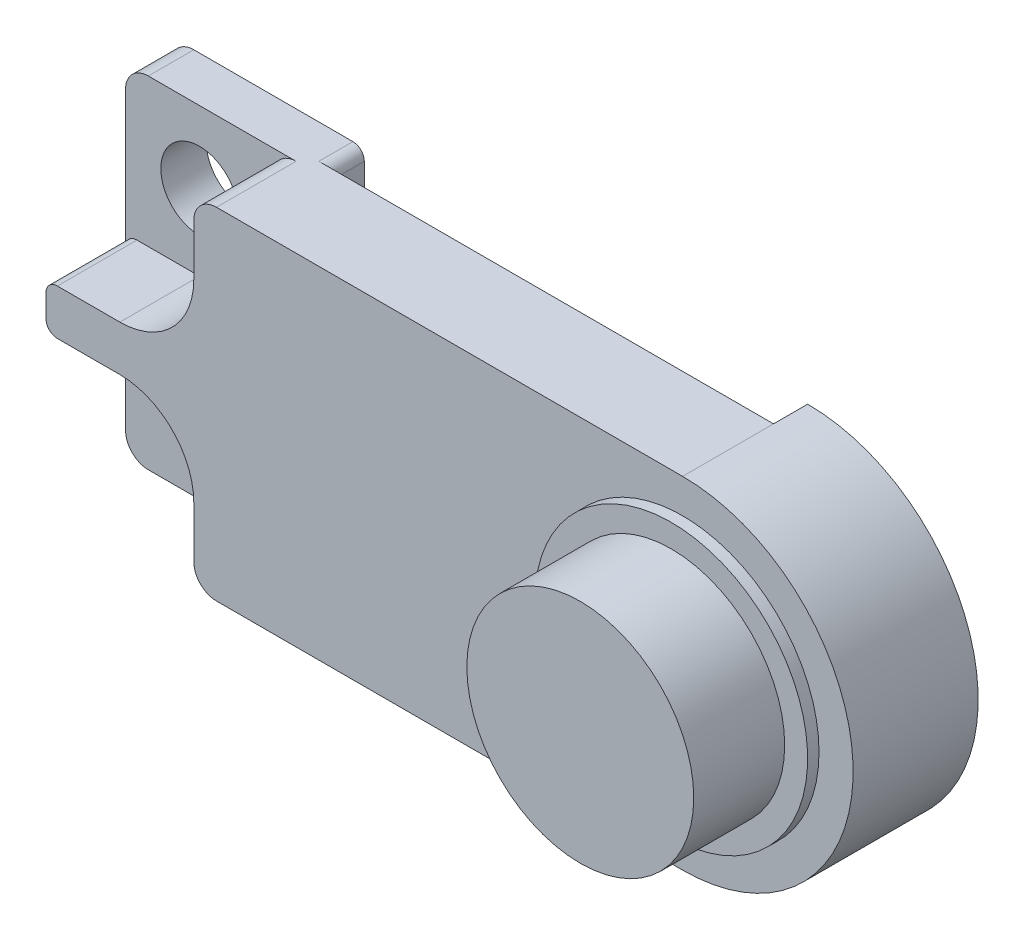
SolidWorks part; units mm, degrees
ref_plane "前视基准面" through (0, 0, 0) normal (0, 0, 1) x (1, 0, 0)
ref_plane "上视基准面" through (0, 0, 0) normal (0, 1, 0) x (1, 0, 0)
ref_plane "右视基准面" through (0, 0, 0) normal (1, 0, 0) x (0, 0, -1)
ref_plane "基准面1" through (0, 0, 5.5) normal (0, 0, 1) x (1, 0, 0)
sketch "草图1" plane through (0, 0, 5.5) normal (0, 0, 1) x (1, 0, 0)
  line L0 (19.5, 5.6661) -> (-8.5, 5.6661)
  line L1 (-8.5, 5.6661) -> (-8.5, -9.3339)
  line L2 (-8.5, -9.3339) -> (19.5, -9.3339)
  arc A0 (19.5, -9.3339) -> (19.5, 5.6661) centre (19.5, -1.8339) ccw
extrude "凸台-拉伸1" add sketch "草图1" against normal blind 5.5
sketch "草图2" plane through (0, -9.3339, 0) normal (0, -1, 0) x (1, 0, 0)
  line L0 (19.5, 1.5) -> (0, 1.5)
  line L1 (0, 1.5) -> (0, 0)
  line L2 (0, 0) -> (19.5, 0)
  line L3 (19.5, 0) -> (19.5, 1.5)
extrude "切除-拉伸1" cut sketch "草图2" against normal through all
sketch "草图3" plane through (0, 5.6661, 0) normal (0, 1, 0) x (-1, 0, 0)
  line L0 (2, 5.5) -> (2, 2)
  line L1 (2, 2) -> (8.5, 2)
  line L2 (8.5, 2) -> (8.5, 5.5)
  line L3 (8.5, 5.5) -> (2, 5.5)
extrude "切除-拉伸2" cut sketch "草图3" against normal blind 6.5
sketch "草图4" plane through (-8.5, 0, 0) normal (-1, 0, 0) x (0, 0, 1)
  line L0 (5.5, -2.8339) -> (2, -2.8339)
  line L1 (2, -2.8339) -> (2, -9.3339)
  line L2 (2, -9.3339) -> (5.5, -9.3339)
  line L3 (5.5, -9.3339) -> (5.5, -2.8339)
extrude "切除-拉伸3" cut sketch "草图4" against normal blind 6.5
ref_plane "基准面2" through (0, -1.8339, 0) normal (0, -1, 0) x (1, 0, 0)
sketch "草图5" plane through (0, -1.8339, 0) normal (0, -1, 0) x (1, 0, 0)
  line L0 (24.49, 10) -> (19.5, 10)
  line L1 (19.5, 10) -> (19.5, 5.5)
  line L2 (19.5, 5.5) -> (25.5, 5.5)
  line L3 (25.5, 5.5) -> (25.5, 6)
  line L4 (25.5, 6) -> (24.49, 6)
  line L5 (24.49, 6) -> (24.49, 10)
  line L6 (19.5, 10) -> (19.5, 5.5) construction
revolve "旋转1" add sketch "草图5" angle 360 about L6
hole_wizard "Ø3.4 (3.4) 直径孔1" positions "草图7" profile "草图6" hole size "Ø3.4" standard "ANSI Metric"
sketch "草图7" plane through (0, 0, 2) normal (0, 0, 1) x (1, 0, 0)
  point P0 (-5.25, 2.4161)
  point P1 (-5.25, -6.0839)
sketch "草图6" plane through (-5.25, 2.4161, 2) normal (1, 0, 0) x (0, -1, 0)
  line L0 (0, 0) -> (0, 2)
  line L1 (0, 2) -> (1.7, 2)
  line L2 (1.7, 2) -> (1.7, 0)
  line L5 (1.7, 0) -> (0, 0)
  line L11 (0, -6.35) -> (0, 107.95) construction
  dimension "通孔孔直径" = 3.4
  dimension "通孔孔深度" = 2
fillet "圆角1" radius 0.5 4 edges at (-8.5, -0.8339, 3.75) (0, 5.6661, 0.75) (-8.5, -2.8339, 3.75) (0, -9.3339, 0.75)
fillet "圆角2" radius 1 4 edges at (-8.5, -9.3339, 1) (-2, 5.6661, 3.75) (-8.5, 5.6661, 1) (-2, -9.3339, 3.75)
fillet "圆角3" radius 3.25 2 edges at (-2, -0.8339, 3.75) (-2, -2.8339, 3.75)
